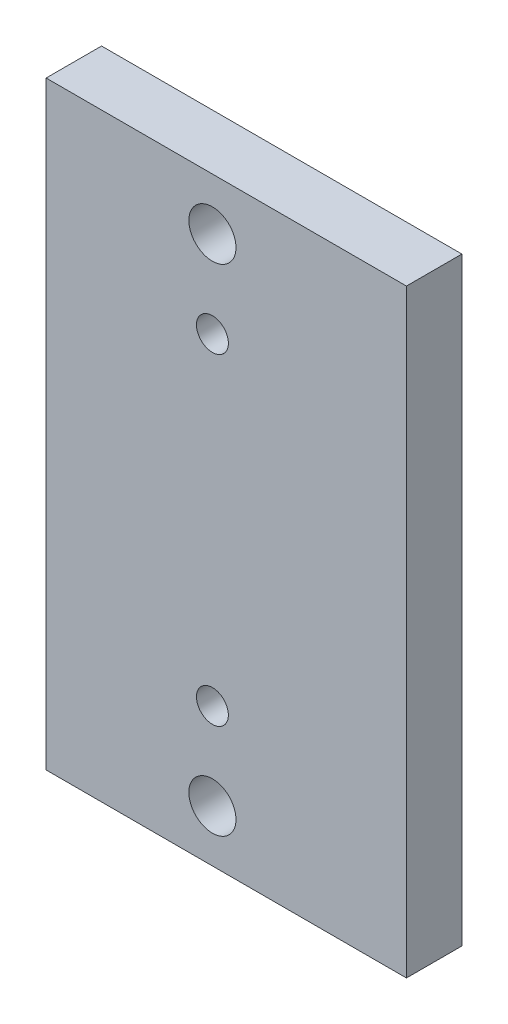
SolidWorks part; units mm, degrees
material "ABS"
ref_plane "Front Plane" through (0, 0, 0) normal (0, 0, 1) x (1, 0, 0)
ref_plane "Top Plane" through (0, 0, 0) normal (0, 1, 0) x (1, 0, 0)
ref_plane "Right Plane" through (0, 0, 0) normal (1, 0, 0) x (0, 0, -1)
sketch "Sketch1" plane through (0, 0, 0) normal (0, 0, 1) x (1, 0, 0)
  line L0 (-4, -16.62) -> (22, -16.62)
  line L1 (22, -16.62) -> (22, 26.62)
  line L2 (22, 26.62) -> (-4, 26.62)
  line L3 (-4, 26.62) -> (-4, -16.62)
  circle A0 centre (8, -12.87) radius 1.7
  circle A1 centre (8, 22.87) radius 1.7
  circle A2 centre (8, -6.62) radius 1.15
  circle A3 centre (8, 16.62) radius 1.15
  dimension "D3" = 3.4
  dimension "D4" = 2.3
  dimension "D1" = 26
  dimension "D2" = 43.24
extrude "Boss-Extrude1" add sketch "Sketch1" along normal blind 4
